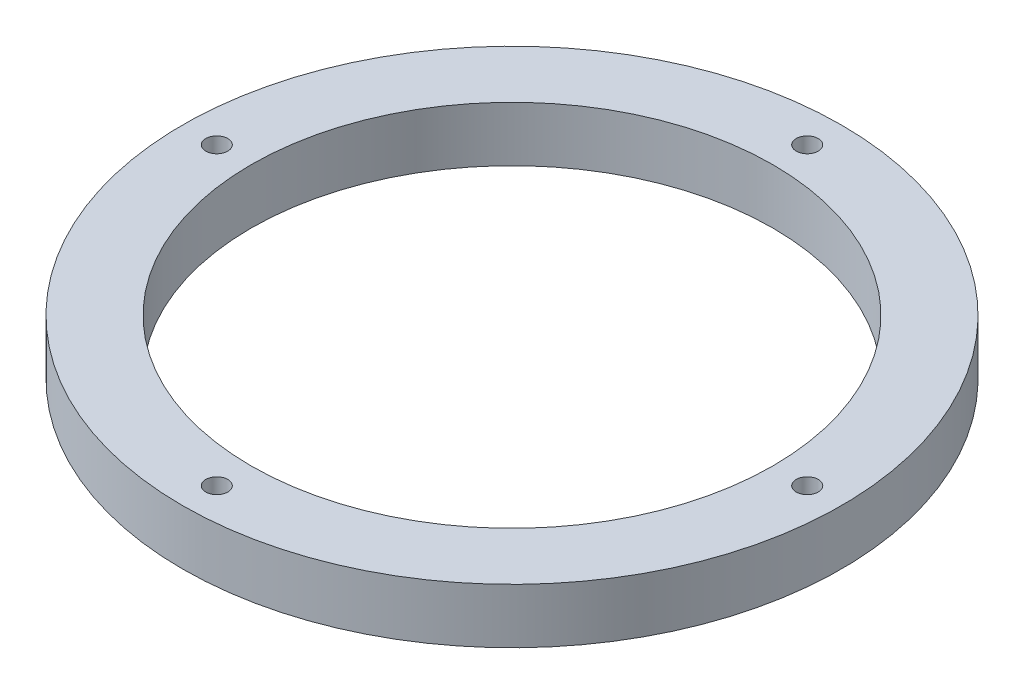
SolidWorks part; units mm, degrees
material "Alumina"
ref_plane "Front Plane" through (0, 0, 0) normal (0, 0, 1) x (1, 0, 0)
ref_plane "Top Plane" through (0, 0, 0) normal (0, 1, 0) x (1, 0, 0)
ref_plane "Right Plane" through (0, 0, 0) normal (1, 0, 0) x (0, 0, -1)
sketch "Sketch1" plane through (0, 0, 0) normal (0, 1, 0) x (1, 0, 0)
  circle A0 centre (0, 0) radius 60
  dimension "D1" = 120
extrude "Boss-Extrude1" add sketch "Sketch1" along normal blind 10
sketch "Sketch2" plane through (0, 10, 0) normal (0, 1, 0) x (1, 0, 0)
  circle A0 centre (0, 0) radius 47.5
  dimension "D1" = 95
extrude "Cut-Extrude1" cut sketch "Sketch2" against normal up to surface (10 mm away) up to face at (0, 0, 60)
sketch "Sketch3" plane through (0, 10, 0) normal (0, 1, 0) x (1, 0, 0)
  line L0 (0, 60) -> (0, -60) construction
  line L2 (-60, 0) -> (60, 0) construction
  circle A0 centre (0, 0) radius 60 construction
sketch "Sketch4" plane through (0, 10, 0) normal (0, 1, 0) x (1, 0, 0)
  line L0 (0, 60) -> (0, -60) construction
  circle A0 centre (0, 53.75) radius 2
  dimension "D1" = 53.75
extrude "Cut-Extrude2" cut sketch "Sketch4" against normal up to surface (10 mm away) up to face at (0, 0, 47.5)
pattern_circular "CirPattern1" count 4 over 360 about axis through (0, 0, 0) along (0, 1, 0) of "Cut-Extrude2"
